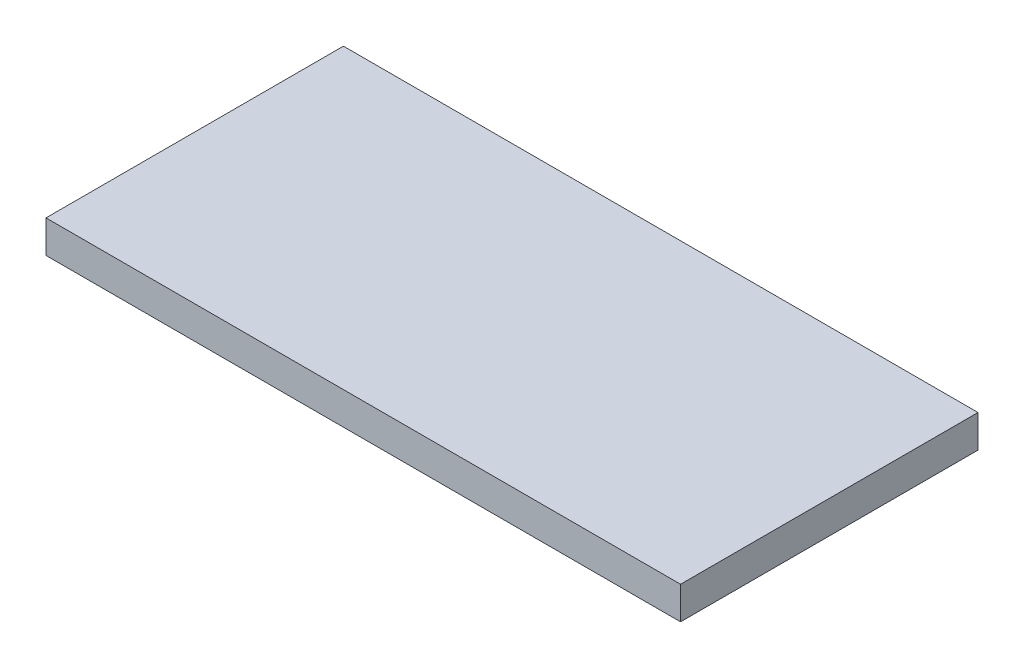
SolidWorks part; units mm, degrees
material "未指定"
ref_plane "正面" through (0, 0, 0) normal (0, 0, 1) x (1, 0, 0)
ref_plane "平面" through (0, 0, 0) normal (0, 1, 0) x (1, 0, 0)
ref_plane "右側面" through (0, 0, 0) normal (1, 0, 0) x (0, 0, -1)
sketch "ｽｹｯﾁ1" plane through (0, 0, 0) normal (0, 1, 0) x (1, 0, 0)
  line L0 (-224, 105) -> (224, 105)
  line L1 (224, 105) -> (224, -105)
  line L2 (224, -105) -> (-224, -105)
  line L3 (-224, -105) -> (-224, 105)
  line L4 (0, 0) -> (0, -25) construction
  line L5 (0, 0) -> (25, 0) construction
  dimension "D1" = 448
  dimension "D2" = 210
extrude "ブロック 切り出し" add sketch "ｽｹｯﾁ1" along normal mid plane 23
equation "\"FOAM_X\" = 224"
equation "\"D1@ｽｹｯﾁ1\" = 2 * ( \"FOAM_X\" )"
equation "\"INNER_HALF_W\" = 105"
equation "\"D2@ｽｹｯﾁ1\" = 2 * ( \"INNER_HALF_W\" )"
equation "\"FOAM_T\" = 23"
equation "\"D1@ブロック 切り出し\" = \"FOAM_T\""
